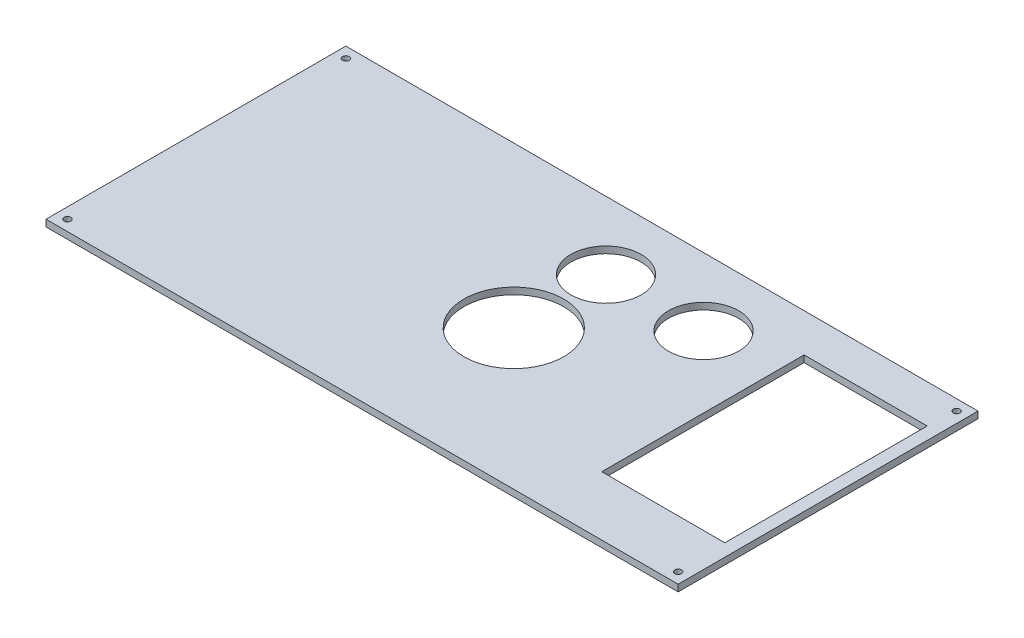
SolidWorks part; units mm, degrees
ref_plane "Front Plane" through (0, 0, 0) normal (0, 0, 1) x (1, 0, 0)
ref_plane "Top Plane" through (0, 0, 0) normal (0, 1, 0) x (1, 0, 0)
ref_plane "Right Plane" through (0, 0, 0) normal (1, 0, 0) x (0, 0, -1)
sketch "Sketch2" plane through (0, 0, 0) normal (0, 1, 0) x (1, 0, 0)
  line L1 (117.945, -55.945) -> (-117.945, -55.945)
  line L2 (117.945, -55.945) -> (117.945, 55.945)
  line L3 (117.945, 55.945) -> (-117.945, 55.945)
  line L4 (-117.945, -55.945) -> (-117.945, 55.945)
  line L5 (117.945, -55.945) -> (-117.945, 55.945) construction
  line L6 (117.945, 55.945) -> (-117.945, -55.945) construction
  point P0 (0, 0)
  dimension "D1" = 235.89
  dimension "D2" = 111.89
extrude "Boss-Extrude1" add sketch "Sketch2" along normal blind 2.5
sketch "Sketch3" plane through (0, 2.5, 0) normal (0, 1, 0) x (1, 0, 0)
  line L0 (-117.945, 55.945) -> (-117.945, -55.945) construction
  line L1 (117.945, 55.945) -> (-117.945, 55.945) construction
  circle A0 centre (-113.945, 51.945) radius 1.25
  circle A1 centre (-113.945, -51.945) radius 1.25
  circle A2 centre (113.945, -51.945) radius 1.25
  circle A3 centre (113.945, 51.945) radius 1.25
  dimension "D3" = 2.5
  dimension "D1" = 4
  dimension "D2" = 4
  dimension "D4" = 2
  dimension "D5" = 2
extrude "Cut-Extrude1" cut sketch "Sketch3" against normal through all
sketch "Sketch4" plane through (0, 2.5, 0) normal (0, 1, 0) x (1, 0, 0)
  line L0 (117.945, -55.945) -> (117.945, 55.945) construction
  line L1 (113.2871, 41.645) -> (67.3583, 41.645)
  line L2 (113.2871, 41.645) -> (113.2871, -33.8537)
  line L3 (113.2871, -33.8537) -> (67.3583, -33.8537)
  line L4 (67.3583, 41.645) -> (67.3583, -33.8537)
  line L6 (117.945, 55.945) -> (-117.945, 55.945) construction
  circle A0 centre (40.845, 30.6237) radius 13.1
  circle A1 centre (4.445, 30.6237) radius 13.1
  circle A2 centre (4.445, -3.7763) radius 18.65
  dimension "D10" = 37.3
  dimension "D11" = 26.2
  dimension "D12" = 26.2
  dimension "D1" = 4.6579
  dimension "D2" = 89.7987
  dimension "D3" = 45.9288
  dimension "D4" = 75.4987
  dimension "D5" = 77.1
  dimension "D6" = 36.4
  dimension "D7" = 25.3213
  dimension "D8" = 113.5
  dimension "D9" = 59.7213
extrude "Cut-Extrude2" cut sketch "Sketch4" against normal through all and the other way through all
